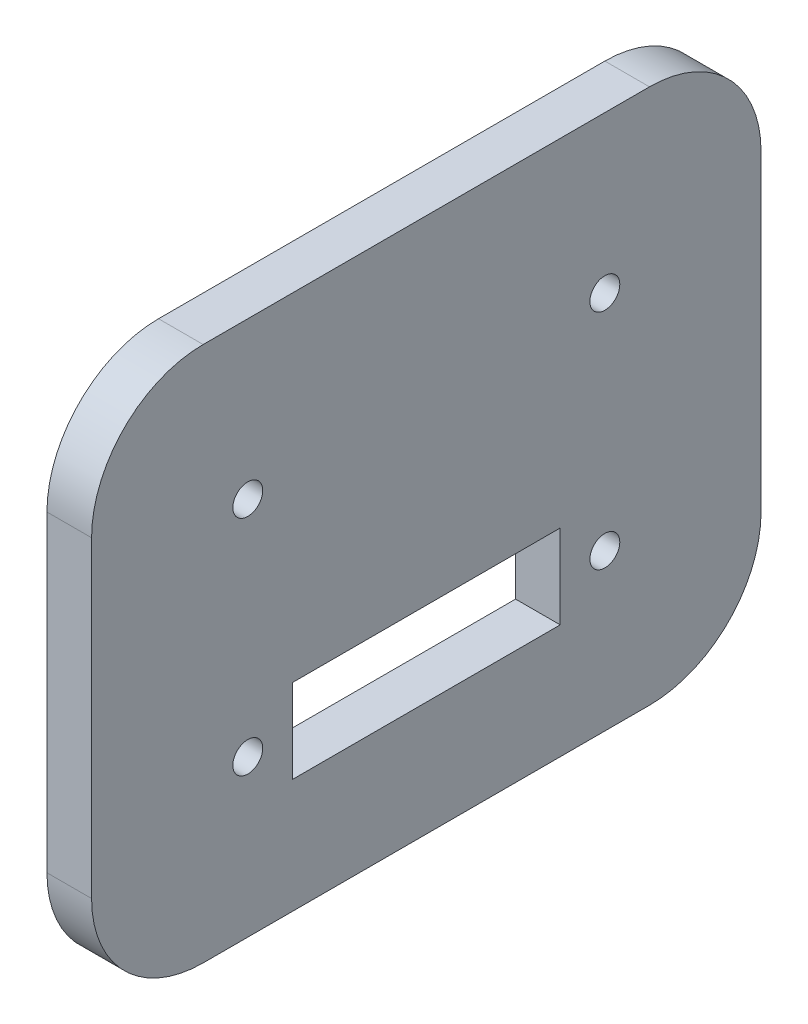
SolidWorks part; units mm, degrees
ref_plane "Front Plane" through (0, 0, 0) normal (0, 0, 1) x (1, 0, 0)
ref_plane "Top Plane" through (0, 0, 0) normal (0, 1, 0) x (1, 0, 0)
ref_plane "Right Plane" through (0, 0, 0) normal (1, 0, 0) x (0, 0, -1)
sketch "Sketch1" plane through (0, 0, 0) normal (1, 0, 0) x (0, 0, -1)
  line L1 (-19.05, -15.24) -> (19.05, -15.24)
  line L2 (-19.05, -15.24) -> (-19.05, 15.24)
  line L3 (-19.05, 15.24) -> (19.05, 15.24)
  line L4 (19.05, -15.24) -> (19.05, 15.24)
  line L5 (-19.05, -15.24) -> (19.05, 15.24) construction
  line L6 (-19.05, 15.24) -> (19.05, -15.24) construction
  point P0 (0, 0)
  dimension "D1" = 38.1
  dimension "D2" = 30.48
extrude "Boss-Extrude1" add sketch "Sketch1" along normal blind 2.54
sketch "Sketch2" plane through (2.54, 0, 0) normal (1, 0, 0) x (0, 0, -1)
  circle A0 centre (10.16, 6.35) radius 0.8509
  dimension "D3" = 1.7018
  dimension "D1" = 6.35
  dimension "D2" = 10.16
extrude "Cut-Extrude1" cut sketch "Sketch2" against normal blind 2.54
mirror "Mirror1" about plane through (0, 0, 0) normal (0, 0, 1) of "Cut-Extrude1"
mirror "Mirror2" about plane through (0, 0, 0) normal (0, 1, 0) of "Cut-Extrude1", "Mirror1"
fillet "Fillet1" radius 6.35 4 edges at (1.27, 15.24, -19.05) (1.27, -15.24, -19.05) (1.27, -15.24, 19.05) (1.27, 15.24, 19.05)
sketch "Sketch3" plane through (2.54, 0, 0) normal (1, 0, 0) x (0, 0, -1)
  line L0 (-10.16, -6.35) -> (10.16, -6.35) construction
  line L2 (-7.62, -8.7376) -> (7.62, -8.7376)
  line L3 (-7.62, -8.7376) -> (-7.62, -3.9624)
  line L4 (-7.62, -3.9624) -> (7.62, -3.9624)
  line L5 (7.62, -8.7376) -> (7.62, -3.9624)
  line L6 (-7.62, -8.7376) -> (7.62, -3.9624) construction
  line L7 (-7.62, -3.9624) -> (7.62, -8.7376) construction
  point P4 (0, -6.35)
  dimension "D1" = 15.24
  dimension "D2" = 4.7752
extrude "Cut-Extrude2" cut sketch "Sketch3" against normal blind 2.54
